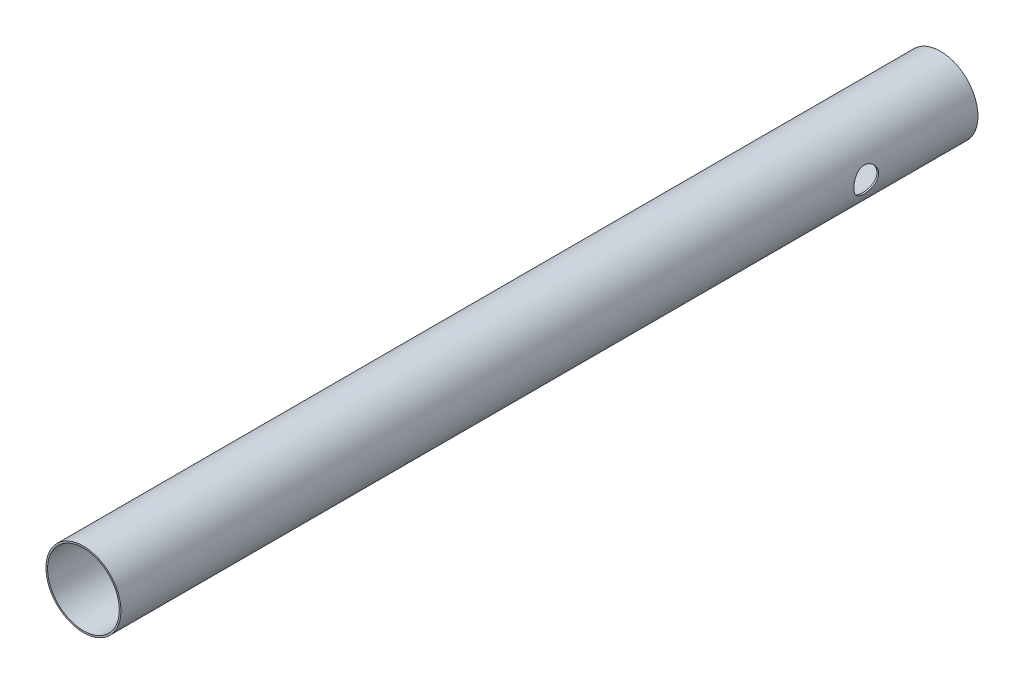
SolidWorks part; units mm, degrees
material "ALUMINUM 6061-T6; 6061-T651"
ref_plane "Front Plane" through (0, 0, 0) normal (0, 0, 1) x (1, 0, 0)
ref_plane "Top Plane" through (0, 0, 0) normal (0, 1, 0) x (1, 0, 0)
ref_plane "Right Plane" through (0, 0, 0) normal (1, 0, 0) x (0, 0, -1)
sketch "Sketch1" plane through (0, 0, 0) normal (0, 0, 1) x (1, 0, 0)
  line L0 (0, 0) -> (36.6776, 0) construction
  line L1 (36.6776, 0) -> (38.354, 0) construction
  circle A0 centre (0, 0) radius 36.6776
  circle A1 centre (0, 0) radius 38.354
  dimension "D1" = 76.708
  dimension "D2" = 1.6764
extrude "Boss-Extrude1" add sketch "Sketch1" along normal blind 762 and the other way blind 114.3
sketch "Sketch2" plane through (0, 0, 0) normal (1, 0, 0) x (0, 0, -1)
  circle A0 centre (0, 0) radius 12.7
  dimension "D1" = 25.4
extrude "Cut-Extrude1" cut sketch "Sketch2" along normal through all
